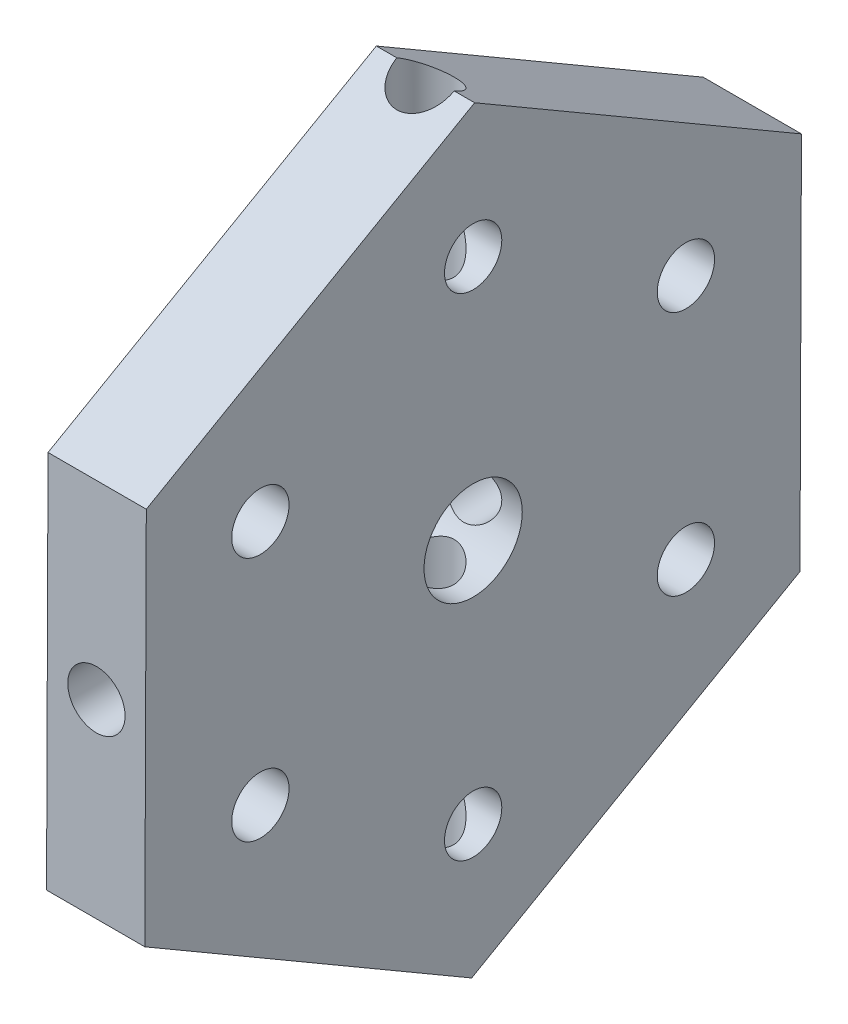
SolidWorks part; units mm, degrees
ref_plane "Plan de face" through (0, 0, 0) normal (0, 0, 1) x (1, 0, 0)
ref_plane "Plan de dessus" through (0, 0, 0) normal (0, 1, 0) x (1, 0, 0)
ref_plane "Plan de droite" through (0, 0, 0) normal (1, 0, 0) x (0, 0, -1)
sketch "Esquisse1" plane through (0, 0, 0) normal (1, 0, 0) x (0, 0, -1)
  line L0 (0, 15) -> (0, -15) construction
  line L1 (-12.9904, 7.5) -> (12.9904, -7.5) construction
  line L2 (12.9904, 7.5) -> (-12.9904, -7.5) construction
  line L4 (-20.0452, -11.4684) -> (-0.0906, -23.0938)
  line L5 (-0.0906, -23.0938) -> (19.9545, -11.6254)
  line L6 (19.9545, -11.6254) -> (20.0452, 11.4684)
  line L7 (20.0452, 11.4684) -> (0.0906, 23.0938)
  line L8 (0.0906, 23.0938) -> (-19.9545, 11.6254)
  line L9 (-19.9545, 11.6254) -> (-20.0452, -11.4684)
  circle A0 centre (0, 0) radius 3
  circle A1 centre (0, 0) radius 20 construction
  circle A2 centre (0, 0) radius 15 construction
  circle A3 centre (0, 15) radius 1.75
  circle A4 centre (12.9904, 7.5) radius 1.75
  circle A5 centre (12.9904, -7.5) radius 1.75
  circle A6 centre (0, -15) radius 1.75
  circle A7 centre (-12.9904, -7.5) radius 1.75
  circle A8 centre (-12.9904, 7.5) radius 1.75
  circle A9 centre (0, 0) radius 16.75 construction
  point P3 (-10.0679, -17.2811)
  dimension "D1" = 40
  dimension "D2" = 6
  dimension "D5" = 30
  dimension "D6" = 3.5
  dimension "D3" = 60
  dimension "D4" = 60
extrude "Boss.-Extru.1" add sketch "Esquisse1" along normal blind 6
sketch "Esquisse2" plane through (0, 0, 0) normal (-1, 0, 0) x (0, 0, 1)
  circle A0 centre (0, 0) radius 10
  circle A1 centre (0, 15) radius 5 construction
  circle A2 centre (0, 0) radius 3
  circle A4 centre (0, 0) radius 3 construction
  dimension "D1" = 10
  dimension "D2" = 20
extrude "Boss.-Extru.2" add sketch "Esquisse2" along normal blind 6
sketch "Esquisse3" plane through (0, 0, 0) normal (0, 1, 0) x (1, 0, 0)
  line L0 (0, 0) -> (-6, 0) construction
  line L1 (-6, 10) -> (-6, -10) construction
  line L2 (6, 0.0906) -> (0, 0.0906) construction
  circle A0 centre (-3, 0) radius 1.75
  circle A1 centre (3, 0.0906) radius 1.75
  dimension "D1" = 3.5
extrude "Enlèv. mat.-Extru.1" cut sketch "Esquisse3" against normal through all and the other way through all
sketch "Esquisse4" plane through (0, 0.0785, 19.9998) normal (0, 0.0039, 1) x (1, 0, 0)
  line L0 (6, 0) -> (0, 0) construction
  line L1 (6, 11.547) -> (6, -11.547) construction
  line L2 (0, 0) -> (-6, 0) construction
  line L3 (-6, 10) -> (-6, -10) construction
  circle A0 centre (3, 0) radius 1.75
  circle A1 centre (-3, 0) radius 1.75
  dimension "D1" = 3.5
extrude "Enlèv. mat.-Extru.2" cut sketch "Esquisse4" against normal through all
